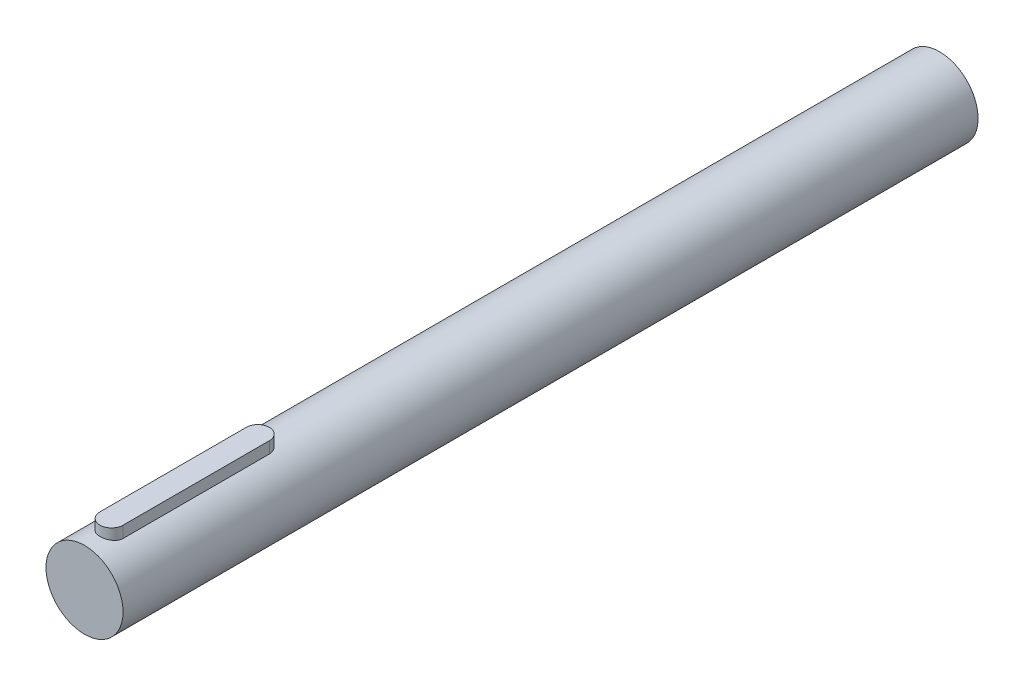
SolidWorks part; units mm, degrees
ref_plane "前视基准面" through (0, 0, 0) normal (0, 0, 1) x (1, 0, 0)
ref_plane "上视基准面" through (0, 0, 0) normal (0, 1, 0) x (1, 0, 0)
ref_plane "右视基准面" through (0, 0, 0) normal (1, 0, 0) x (0, 0, -1)
sketch "草图1" plane through (0, 0, 0) normal (0, 0, 1) x (1, 0, 0)
  circle A1 centre (0, 0) radius 5
  dimension "D1" = 10
extrude "凸台-拉伸1" add sketch "草图1" along normal blind 26
sketch "草图3" plane through (0, 0, 0) normal (0, 0, -1) x (-1, 0, 0)
  circle A0 centre (0, 0) radius 5
extrude "凸台-拉伸3" add sketch "草图3" along normal blind 85
ref_plane "基准面1" through (0, 6.269, 0) normal (0, 1, 0) x (1, 0, 0)
sketch "草图5" plane through (0, 6.269, 0) normal (0, 1, 0) x (1, 0, 0)
  line L8 (1.5, -3.5) -> (1.5, -22.5)
  line L9 (-1.5, -3.5) -> (-1.5, -22.5)
  arc A0 (1.5, -3.5) -> (-1.5, -3.5) centre (0, -3.5) ccw
  arc A1 (-1.5, -22.5) -> (1.5, -22.5) centre (0, -22.5) ccw
extrude "凸台-拉伸4" add sketch "草图5" against normal up to next
